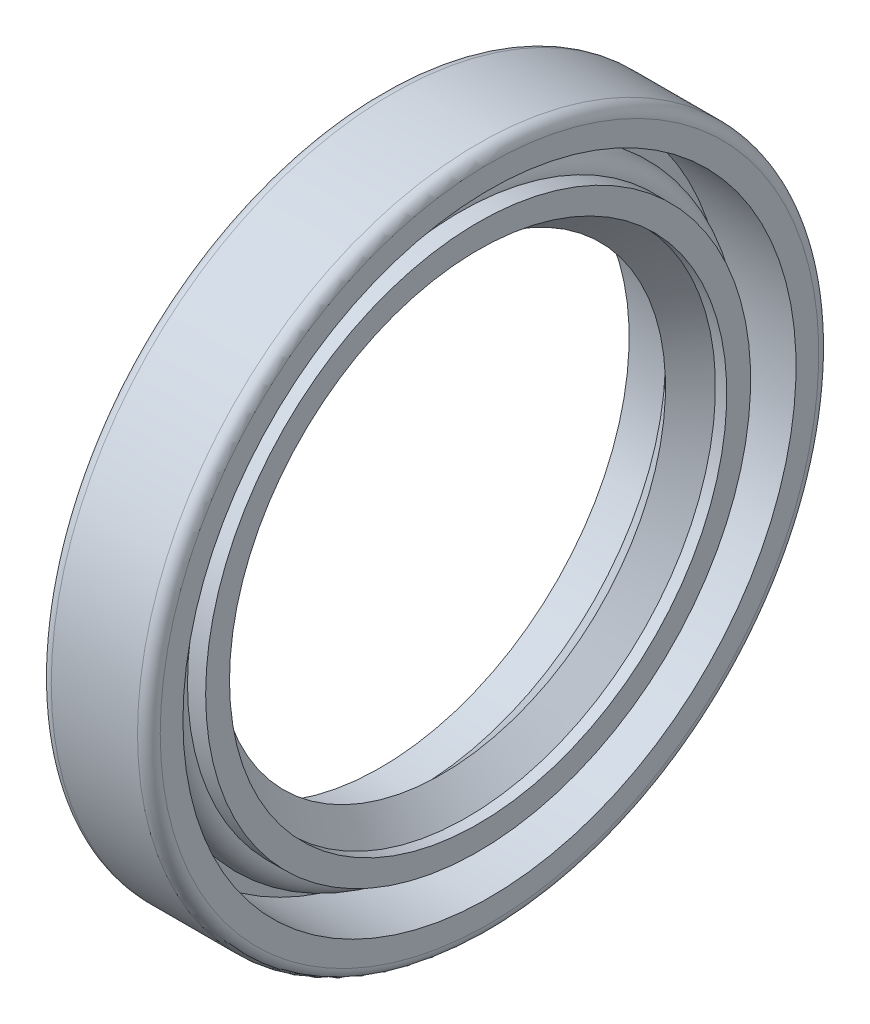
SolidWorks part; units mm, degrees
material "Rubber"
ref_plane "Front Plane" through (0, 0, 0) normal (0, 0, 1) x (1, 0, 0)
ref_plane "Top Plane" through (0, 0, 0) normal (0, 1, 0) x (1, 0, 0)
ref_plane "Right Plane" through (0, 0, 0) normal (1, 0, 0) x (0, 0, -1)
sketch "Primary Sketch" plane through (0, 0, 0) normal (0, 0, 1) x (1, 0, 0)
  line L0 (0, 0) -> (0, 17.145) construction
  line L13 (2.032, 17.145) -> (6.096, 17.145)
  line L14 (0, 17.145) -> (0, 19.05)
  line L15 (0, 19.05) -> (6.096, 19.05)
  line L16 (6.096, 17.145) -> (6.096, 19.05)
  line L17 (2.032, 13.9065) -> (2.032, 12.5095) construction
  line L19 (0, 17.145) -> (0, 13.9065)
  line L20 (0, 13.9065) -> (2.032, 13.9065)
  line L21 (2.032, 17.145) -> (2.032, 15.24)
  line L22 (2.032, 15.24) -> (2.413, 15.24)
  line L24 (4.826, 13.9065) -> (5.461, 13.9065)
  line L25 (5.461, 15.24) -> (5.461, 13.9065)
  line L26 (2.032, 13.9065) -> (3.429, 12.5095)
  line L27 (3.429, 12.5095) -> (4.826, 13.9065)
  line L28 (4.445, 15.24) -> (5.461, 15.24)
  line L29 (0, 0) -> (3.429, 0) construction
  line L30 (0, 0) -> (8.5999, 0) construction
  arc A0 (4.445, 15.24) -> (2.413, 15.24) centre (3.429, 15.24) ccw
  point P12 (3.429, 15.24)
  dimension "D5" = 5.461
  dimension "D10" = 2.032
  dimension "D1" = 6.096
  dimension "D2" = 5.1435
  dimension "D3" = 3.2385
  dimension "D4" = 2.032
  dimension "D6" = 13.9065
  dimension "D7" = 3.81
  dimension "D8" = 1.397
  dimension "D9" = 1.397
  dimension "D11" = 1.397
  dimension "D12" = 4.064
  dimension "D13" = 1.905
revolve "Primary Revolve" add sketch "Primary Sketch" angle 360 about L30
fillet "Edge Fillet" radius 0.635 2 edges at (0, 0, 19.05) (6.096, 0, 19.05)
